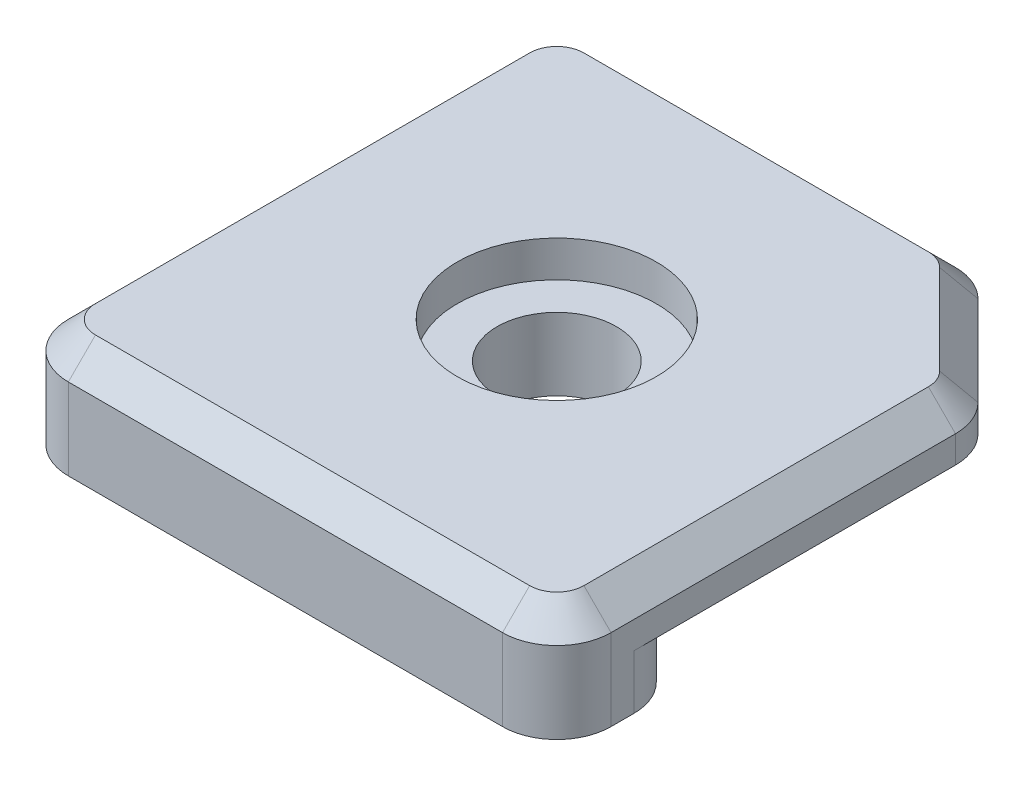
SolidWorks part; units mm, degrees
ref_plane "Frente" through (0, 0, 0) normal (0, 0, 1) x (1, 0, 0)
ref_plane "Topo" through (0, 0, 0) normal (0, 1, 0) x (1, 0, 0)
ref_plane "Lateral" through (0, 0, 0) normal (1, 0, 0) x (0, 0, -1)
sketch "Sketch1" plane through (0, 0, 0) normal (0, 1, 0) x (1, 0, 0)
  line L1 (-15, 15) -> (15, 15)
  line L2 (-15, 15) -> (-15, -15)
  line L3 (-15, -15) -> (15, -15)
  line L4 (15, 15) -> (15, -15)
  line L5 (-15, 15) -> (15, -15) construction
  line L6 (-15, -15) -> (15, 15) construction
  point P0 (0, 0)
  dimension "D1" = 30
extrude "Boss-Extrude1" add sketch "Sketch1" along normal blind 6
sketch "Sketch2" plane through (0, 0, 0) normal (0, -1, 0) x (1, 0, 0)
  line L0 (15, 9.5) -> (-9.5, -15)
  line L1 (15, 15) -> (15, -15) construction
  line L2 (15, -15) -> (-15, -15) construction
  line L3 (-9.5, -15) -> (15, -15)
  line L4 (15, -15) -> (15, 9.5)
  dimension "D1" = 24.5
extrude "Cut-Extrude1" cut sketch "Sketch2" against normal blind 3
sketch "Sketch3" plane through (0, 3, 0) normal (0, -1, 0) x (1, 0, 0)
  line L0 (15, -8.2825) -> (15, -15)
  line L2 (15, -15) -> (8.2825, -15)
  line L3 (-9.5, -15) -> (15, -15) construction
  line L4 (8.2825, -15) -> (15, -8.2825)
  line L8 (15, 9.5) -> (-9.5, -15) construction
  point P12 (0, 0)
  dimension "D1" = 9.5
extrude "Cut-Extrude2" cut sketch "Sketch3" against normal through all
fillet "Fillet1" radius 3 7 edges at (-15, 3, 15) (-15, 3, -15) (8.2825, 4.5, -15) (15, 4.5, -8.2825) (15, 3, 15) (15, 1.5, 9.5) (-9.5, 1.5, -15)
chamfer "Chamfer1" distance 1.5 angle 45 10 edges at (-14.1213, 6, -14.1213) (-2.4801, 6, -15) (8.1879, 6, -14.7716) (11.6412, 6, -11.6412) (14.7716, 6, -8.1879) (15, 6, 2.4801) (14.1213, 6, 14.1213) (0, 6, 15) (-14.1213, 6, 14.1213) (-15, 6, 0)
hole_wizard "CBORE for M6 Hex Socket Head Cap Screw1" positions "Sketch4" profile "Sketch5" counterbore size "M6" standard "DIN" end condition through all
sketch "Sketch4" plane through (0, 6, 0) normal (0, 1, 0) x (1, 0, 0)
  point P0 (0, 0)
sketch "Sketch5" plane through (0, 6, 0) normal (1, 0, 0) x (0, 0, 1)
  line L0 (0, 0) -> (0, 6)
  line L1 (0, 6) -> (3.3, 6)
  line L3 (3.3, 6) -> (3.3, 2)
  line L4 (3.3, 2) -> (5.5, 2)
  line L5 (5.5, 2) -> (5.5, 0)
  line L7 (5.5, 0) -> (0, 0)
  line L11 (0, -6.35) -> (0, 107.95) construction
  dimension "Thru Hole Dia." = 6.6
  dimension "Thru Hole Depth" = 6
  dimension "C'Bore Dia." = 11
  dimension "C'Bore Depth" = 2
